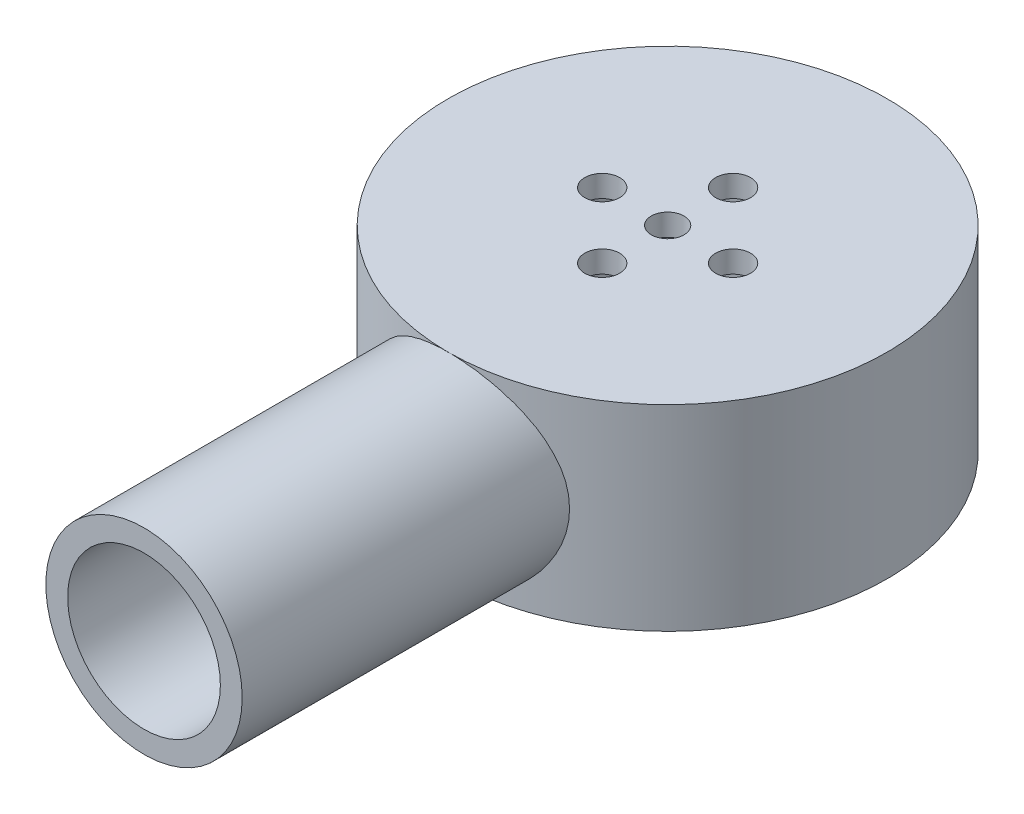
SolidWorks part; units mm, degrees
material "PLA"
ref_plane "Front Plane" through (0, 0, 0) normal (0, 0, 1) x (1, 0, 0)
ref_plane "Top Plane" through (0, 0, 0) normal (0, 1, 0) x (1, 0, 0)
ref_plane "Right Plane" through (0, 0, 0) normal (1, 0, 0) x (0, 0, -1)
sketch "Sketch1" plane through (0, 0, 0) normal (0, 0, 1) x (1, 0, 0)
  circle A0 centre (0, 0) radius 7
  circle A1 centre (0, 0) radius 9
  dimension "D1" = 14
  dimension "D2" = 2
extrude "Boss-Extrude1" add sketch "Sketch1" against normal blind 30 contours A1 A0
sketch "Sketch3" plane through (0, 0, 0) normal (0, 1, 0) x (1, 0, 0)
  line L0 (7, 30) -> (-7, 30) construction
  line L1 (0, 48) -> (0, 30) construction
  circle A0 centre (0, 48) radius 20.1246
  circle A1 centre (0, 48) radius 6 construction
  circle A2 centre (0, 54) radius 1.6
  circle A3 centre (6, 48) radius 1.6
  circle A4 centre (-6, 48) radius 1.6
  circle A5 centre (0, 42) radius 1.6
  circle A6 centre (0, 48) radius 1.5
  dimension "D2" = 12
  dimension "D3" = 3.2
  dimension "D4" = 3
  dimension "D1" = 18
extrude "Boss-Extrude2" add sketch "Sketch3" against normal blind 18 from offset 9 separate body contours A0 A6 A5 A4 A3 A2
sketch "Sketch4" plane through (0, -9, 0) normal (0, -1, 0) x (1, 0, 0)
  circle A0 centre (0, -48) radius 18.1246
  circle A1 centre (0, -48) radius 20.1246 construction
  dimension "D1" = 2
extrude "Cut-Extrude1" cut sketch "Sketch4" against normal blind 16
equation "\"DD_ShaftDiameterMm\"= 3"
equation "\"DD_BoltCircleMm\"= 12"
equation "\"DD_BoltHoleDiameterMm\"= 3.2"
equation "\"DD_MotorOuterDiameterMm\"= 36"
equation "\"DD_ArmTubeOdMm\"= 14"
equation "\"D1@Sketch1\"=\"DD_ArmTubeOdMm\""
equation "\"D1@Sketch3\"=\"DD_MotorOuterDiameterMm\"/2"
equation "\"D2@Sketch3\"=\"DD_BoltCircleMm\""
equation "\"D3@Sketch3\"=\"DD_BoltHoleDiameterMm\""
equation "\"D4@Sketch3\"=\"DD_ShaftDiameterMm\""
equation "\"D19@Boss-Extrude2\"=(\"DD_ArmTubeOdMm\"/2)+2"
equation "\"D1@Boss-Extrude2\"=\"DD_ArmTubeOdMm\"+4"
equation "\"D1@Cut-Extrude1\"=\"DD_ArmTubeOdMm\"+2"
